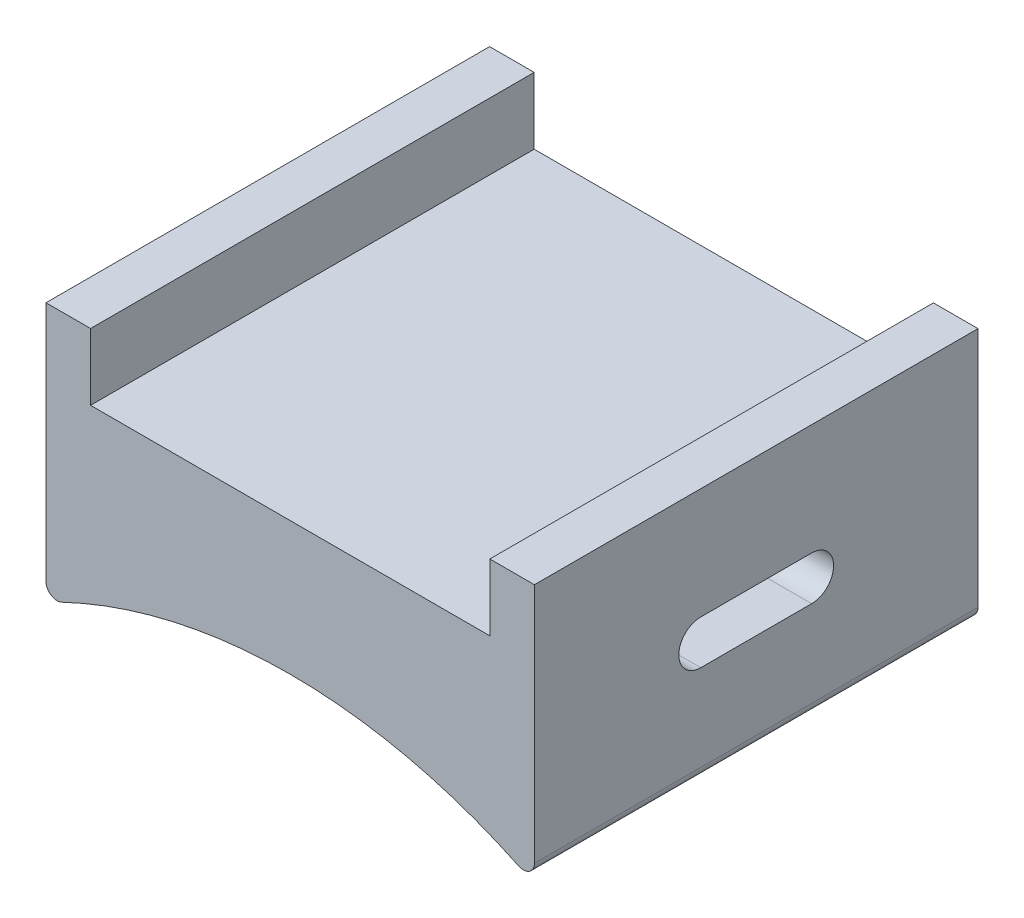
SolidWorks part; units mm, degrees
ref_plane "Front Plane" through (0, 0, 0) normal (0, 0, 1) x (1, 0, 0)
ref_plane "Top Plane" through (0, 0, 0) normal (0, 1, 0) x (1, 0, 0)
ref_plane "Right Plane" through (0, 0, 0) normal (1, 0, 0) x (0, 0, -1)
sketch "Sketch1" plane through (0, 0, 0) normal (0, 0, 1) x (1, 0, 0)
  line L0 (-9, 3) -> (9, 3)
  line L1 (-9, 3) -> (-9, 6)
  line L2 (9, 3) -> (9, 6)
  line L4 (-11.01, 6) -> (-11.01, -4.8839)
  line L5 (-9, 6) -> (-11.01, 6)
  line L6 (11.01, 6) -> (9, 6)
  line L7 (11.01, 6) -> (11.01, -4.8839)
  arc A0 (10.2943, -5.335) -> (-10.2943, -5.335) centre (0, -26.86) ccw
  arc A1 (10.2943, -5.335) -> (11.01, -4.8839) centre (10.51, -4.8839) ccw
  arc A2 (-10.2943, -5.335) -> (-11.01, -4.8839) centre (-10.51, -4.8839) cw
extrude "Boss-Extrude1" add sketch "Sketch1" along normal blind 20
sketch "Sketch2" plane through (11.01, 0, 0) normal (1, 0, 0) x (0, 0, -1)
  line L3 (-12.5, 0.99) -> (-7.5, 0.99)
  line L5 (-12.5, -0.99) -> (-7.5, -0.99)
  arc A0 (-12.5, 0.99) -> (-12.5, -0.99) centre (-12.5, 0) ccw
  arc A1 (-7.5, -0.99) -> (-7.5, 0.99) centre (-7.5, 0) ccw
extrude "Cut-Extrude1" cut sketch "Sketch2" against normal up to surface (22.02 mm away) up to face at (-11.01, 0.5581, 10)
